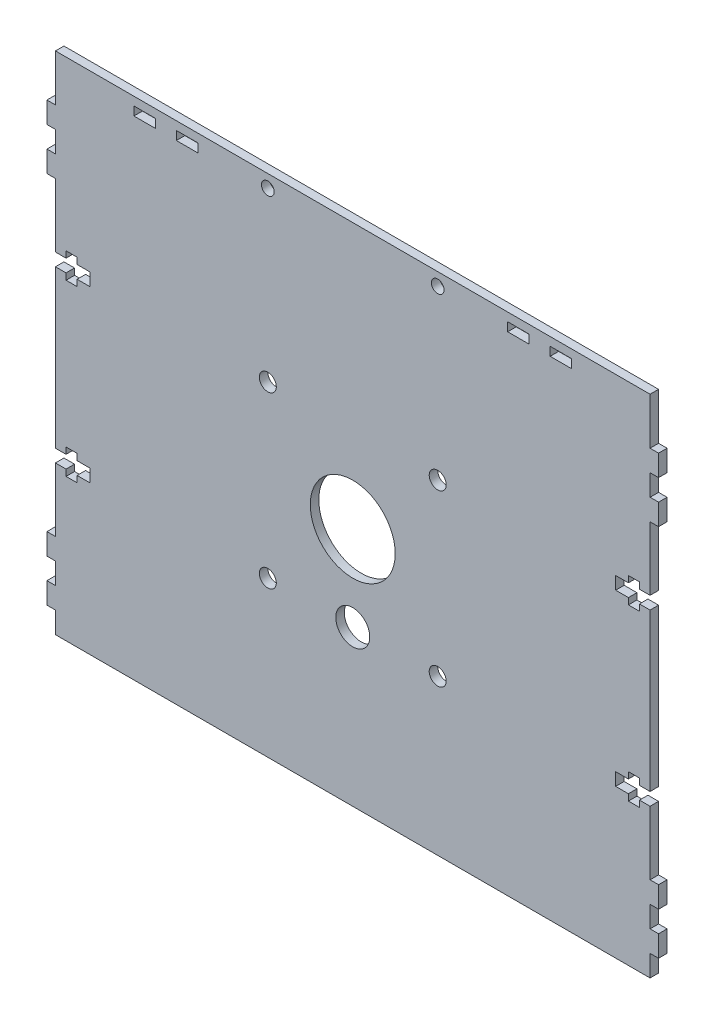
SolidWorks part; units mm, degrees
ref_plane "前视基准面" through (0, 0, 0) normal (0, 0, 1) x (1, 0, 0)
ref_plane "上视基准面" through (0, 0, 0) normal (0, 1, 0) x (1, 0, 0)
ref_plane "右视基准面" through (0, 0, 0) normal (1, 0, 0) x (0, 0, -1)
sketch "草图1" plane through (0, 0, 0) normal (0, 0, 1) x (1, 0, 0)
  line L50 (249.9534, 275.9629) -> (249.9534, 255.9629) construction
  line L53 (317.4534, 257.4629) -> (317.4534, 258.9629)
  line L54 (317.4534, 254.4629) -> (317.4534, 252.9629)
  line L55 (319.9534, 254.4629) -> (317.4534, 254.4629)
  line L56 (317.4534, 258.9629) -> (314.8534, 258.9629)
  line L57 (314.8534, 258.9629) -> (314.8534, 257.4629)
  line L58 (314.8534, 257.4629) -> (311.8534, 257.4629)
  line L59 (311.8534, 254.4629) -> (311.8534, 257.4629)
  line L60 (314.8534, 254.4629) -> (311.8534, 254.4629)
  line L61 (314.8534, 252.9629) -> (314.8534, 254.4629)
  line L62 (317.4534, 252.9629) -> (314.8534, 252.9629)
  line L63 (317.4534, 257.4629) -> (319.9534, 257.4629)
  line L68 (319.9534, 254.4629) -> (319.9534, 257.4629) construction
  line L69 (311.8534, 255.9629) -> (319.9534, 255.9629) construction
  line L73 (311.8534, 295.9629) -> (319.9534, 295.9629) construction
  line L75 (317.4534, 294.4629) -> (319.9534, 294.4629)
  line L76 (317.4534, 298.9629) -> (314.8534, 298.9629)
  line L77 (314.8534, 298.9629) -> (314.8534, 297.4629)
  line L78 (314.8534, 297.4629) -> (311.8534, 297.4629)
  line L79 (311.8534, 297.4629) -> (311.8534, 294.4629)
  line L80 (314.8534, 294.4629) -> (311.8534, 294.4629)
  line L81 (314.8534, 292.9629) -> (314.8534, 294.4629)
  line L82 (317.4534, 292.9629) -> (314.8534, 292.9629)
  line L83 (319.9534, 297.4629) -> (317.4534, 297.4629)
  line L84 (317.4534, 297.4629) -> (317.4534, 298.9629)
  line L85 (317.4534, 294.4629) -> (317.4534, 292.9629)
  line L111 (182.4534, 294.4629) -> (182.4534, 292.9629)
  line L112 (182.4534, 297.4629) -> (182.4534, 298.9629)
  line L113 (179.9534, 297.4629) -> (182.4534, 297.4629)
  line L114 (182.4534, 292.9629) -> (185.0534, 292.9629)
  line L115 (185.0534, 292.9629) -> (185.0534, 294.4629)
  line L116 (185.0534, 294.4629) -> (188.0534, 294.4629)
  line L117 (188.0534, 297.4629) -> (188.0534, 294.4629)
  line L118 (185.0534, 297.4629) -> (188.0534, 297.4629)
  line L119 (185.0534, 298.9629) -> (185.0534, 297.4629)
  line L120 (182.4534, 298.9629) -> (185.0534, 298.9629)
  line L121 (182.4534, 294.4629) -> (179.9534, 294.4629)
  line L122 (182.4534, 257.4629) -> (179.9534, 257.4629)
  line L123 (182.4534, 252.9629) -> (185.0534, 252.9629)
  line L124 (185.0534, 252.9629) -> (185.0534, 254.4629)
  line L125 (185.0534, 254.4629) -> (188.0534, 254.4629)
  line L126 (188.0534, 254.4629) -> (188.0534, 257.4629)
  line L127 (185.0534, 257.4629) -> (188.0534, 257.4629)
  line L128 (185.0534, 258.9629) -> (185.0534, 257.4629)
  line L129 (182.4534, 258.9629) -> (185.0534, 258.9629)
  line L130 (179.9534, 254.4629) -> (182.4534, 254.4629)
  line L131 (182.4534, 254.4629) -> (182.4534, 252.9629)
  line L132 (182.4534, 257.4629) -> (182.4534, 258.9629)
  line L133 (179.9534, 297.4629) -> (179.9534, 294.4629) construction
  line L134 (188.0534, 295.9629) -> (179.9534, 295.9629) construction
  line L135 (188.0534, 255.9629) -> (179.9534, 255.9629) construction
  line L163 (179.9534, 294.4629) -> (179.9534, 257.4629)
  line L172 (319.9534, 257.4629) -> (319.9534, 294.4629)
  line L188 (179.9534, 239.4629) -> (177.9534, 239.4629)
  line L189 (177.9534, 239.4629) -> (177.9534, 234.4629)
  line L190 (177.9534, 234.4629) -> (179.9534, 234.4629)
  line L191 (179.9534, 234.4629) -> (179.9534, 229.4629)
  line L192 (179.9534, 229.4629) -> (177.9534, 229.4629)
  line L193 (177.9534, 229.4629) -> (177.9534, 224.4629)
  line L194 (177.9534, 224.4629) -> (179.9534, 224.4629)
  line L196 (179.9534, 327.4629) -> (179.9534, 345.9629) construction
  line L197 (177.9534, 327.4629) -> (179.9534, 327.4629)
  line L198 (177.9534, 322.4629) -> (177.9534, 327.4629)
  line L199 (179.9534, 322.4629) -> (177.9534, 322.4629)
  line L200 (179.9534, 317.4629) -> (179.9534, 322.4629)
  line L201 (177.9534, 317.4629) -> (179.9534, 317.4629)
  line L202 (177.9534, 312.4629) -> (177.9534, 317.4629)
  line L203 (179.9534, 312.4629) -> (177.9534, 312.4629)
  line L224 (319.9534, 312.4629) -> (321.9534, 312.4629)
  line L225 (321.9534, 312.4629) -> (321.9534, 317.4629)
  line L226 (321.9534, 317.4629) -> (319.9534, 317.4629)
  line L227 (319.9534, 317.4629) -> (319.9534, 322.4629)
  line L228 (319.9534, 322.4629) -> (321.9534, 322.4629)
  line L229 (321.9534, 322.4629) -> (321.9534, 327.4629)
  line L230 (321.9534, 327.4629) -> (319.9534, 327.4629)
  line L233 (321.9534, 224.4629) -> (319.9534, 224.4629)
  line L234 (321.9534, 229.4629) -> (321.9534, 224.4629)
  line L235 (319.9534, 229.4629) -> (321.9534, 229.4629)
  line L236 (319.9534, 234.4629) -> (319.9534, 229.4629)
  line L237 (321.9534, 234.4629) -> (319.9534, 234.4629)
  line L238 (321.9534, 239.4629) -> (321.9534, 234.4629)
  line L239 (319.9534, 239.4629) -> (321.9534, 239.4629)
  line L261 (249.9534, 255.9629) -> (229.9534, 255.9629) construction
  line L262 (319.9534, 327.4629) -> (319.9534, 330.9829)
  line L268 (179.9534, 297.4629) -> (179.9534, 312.4629)
  line L271 (319.9534, 312.4629) -> (319.9534, 297.4629)
  line L272 (319.9534, 254.4629) -> (319.9534, 239.4629)
  line L275 (179.9534, 239.4629) -> (179.9534, 254.4629)
  line L279 (317.4534, 330.9829) -> (317.4534, 345.9629) construction
  line L280 (317.4534, 345.9629) -> (179.9534, 345.9629) construction
  line L285 (317.4534, 338.4729) -> (179.9534, 338.4729)
  line L286 (179.9534, 327.4629) -> (179.9534, 338.4729)
  line L288 (317.4534, 338.4729) -> (319.9534, 338.4729)
  line L289 (319.9534, 338.4729) -> (319.9534, 330.9829)
  line L290 (319.9534, 219.4409) -> (179.9534, 219.4409)
  line L291 (179.9534, 219.4409) -> (179.9534, 224.4629)
  line L292 (319.9534, 219.4409) -> (319.9534, 224.4629)
  line L310 (203.4784, 334.4379) -> (198.4284, 336.4879) construction
  line L311 (286.4284, 336.4879) -> (291.4784, 336.4879)
  line L312 (286.4284, 336.4879) -> (286.4284, 334.4379)
  line L313 (286.4284, 334.4379) -> (291.4784, 334.4379)
  line L314 (291.4784, 336.4879) -> (291.4784, 334.4379)
  line L315 (286.4284, 336.4879) -> (291.4784, 334.4379) construction
  line L316 (286.4284, 334.4379) -> (291.4784, 336.4879) construction
  line L317 (296.4284, 336.4879) -> (301.4784, 336.4879)
  line L318 (296.4284, 336.4879) -> (296.4284, 334.4379)
  line L319 (296.4284, 334.4379) -> (301.4784, 334.4379)
  line L320 (301.4784, 336.4879) -> (301.4784, 334.4379)
  line L321 (296.4284, 336.4879) -> (301.4784, 334.4379) construction
  line L322 (296.4284, 334.4379) -> (301.4784, 336.4879) construction
  line L323 (268.4534, 343.4629) -> (266.9534, 343.4629) [skipped]
  line L324 (271.4534, 343.4629) -> (272.9534, 343.4629) [skipped]
  line L325 (271.4534, 345.9629) -> (271.4534, 343.4629) [skipped]
  line L326 (266.9534, 343.4629) -> (266.9534, 340.8629) [skipped]
  line L327 (266.9534, 340.8629) -> (268.4534, 340.8629) [skipped]
  line L328 (268.4534, 340.8629) -> (268.4534, 337.8629) [skipped]
  line L329 (271.4534, 340.8629) -> (271.4534, 337.8629) [skipped]
  line L330 (272.9534, 340.8629) -> (271.4534, 340.8629) [skipped]
  line L331 (272.9534, 343.4629) -> (272.9534, 340.8629) [skipped]
  line L332 (268.4534, 343.4629) -> (268.4534, 345.9629) [skipped]
  line L333 (231.4534, 343.4629) -> (231.4534, 345.9629) [skipped]
  line L334 (226.9534, 343.4629) -> (226.9534, 340.8629) [skipped]
  line L335 (226.9534, 340.8629) -> (228.4534, 340.8629) [skipped]
  line L336 (228.4534, 340.8629) -> (228.4534, 337.8629) [skipped]
  line L337 (231.4534, 340.8629) -> (231.4534, 337.8629) [skipped]
  line L338 (232.9534, 340.8629) -> (231.4534, 340.8629) [skipped]
  line L339 (232.9534, 343.4629) -> (232.9534, 340.8629) [skipped]
  line L340 (228.4534, 345.9629) -> (228.4534, 343.4629) [skipped]
  line L341 (228.4534, 343.4629) -> (226.9534, 343.4629) [skipped]
  line L342 (231.4534, 343.4629) -> (232.9534, 343.4629) [skipped]
  line L343 (268.4534, 345.9629) -> (231.4534, 345.9629) [skipped]
  line L344 (213.4534, 345.9629) -> (213.4534, 347.9629) [skipped]
  line L345 (213.4534, 347.9629) -> (208.4534, 347.9629) [skipped]
  line L346 (208.4534, 347.9629) -> (208.4534, 345.9629) [skipped]
  line L347 (208.4534, 345.9629) -> (203.4534, 345.9629) [skipped]
  line L348 (203.4534, 345.9629) -> (203.4534, 347.9629) [skipped]
  line L349 (203.4534, 347.9629) -> (198.4534, 347.9629) [skipped]
  line L350 (198.4534, 347.9629) -> (198.4534, 345.9629) [skipped]
  line L352 (301.4534, 345.9629) -> (319.9534, 345.9629) [skipped]
  line L353 (301.4534, 347.9629) -> (301.4534, 345.9629) [skipped]
  line L354 (296.4534, 347.9629) -> (301.4534, 347.9629) [skipped]
  line L355 (296.4534, 345.9629) -> (296.4534, 347.9629) [skipped]
  line L356 (291.4534, 345.9629) -> (296.4534, 345.9629) [skipped]
  line L357 (291.4534, 347.9629) -> (291.4534, 345.9629) [skipped]
  line L358 (286.4534, 347.9629) -> (291.4534, 347.9629) [skipped]
  line L359 (286.4534, 345.9629) -> (286.4534, 347.9629) [skipped]
  line L360 (271.4534, 345.9629) -> (268.4534, 345.9629) construction
  line L361 (269.9534, 337.8629) -> (269.9534, 345.9629) construction
  line L362 (229.9534, 337.8629) -> (229.9534, 345.9629) construction
  line L363 (271.4534, 337.8629) -> (268.4534, 337.8629) [skipped]
  line L364 (228.4534, 337.8629) -> (231.4534, 337.8629) [skipped]
  line L365 (203.4784, 336.4879) -> (198.4284, 334.4379) construction
  line L366 (213.4784, 334.4379) -> (208.4284, 336.4879) construction
  line L367 (213.4784, 336.4879) -> (208.4284, 334.4379) construction
  line L368 (198.4284, 336.4879) -> (198.4284, 334.4379)
  line L369 (203.4784, 334.4379) -> (198.4284, 334.4379)
  line L370 (203.4784, 336.4879) -> (203.4784, 334.4379)
  line L371 (203.4784, 336.4879) -> (198.4284, 336.4879)
  line L372 (208.4284, 336.4879) -> (208.4284, 334.4379)
  line L373 (213.4784, 334.4379) -> (208.4284, 334.4379)
  line L374 (213.4784, 336.4879) -> (213.4784, 334.4379)
  line L375 (213.4784, 336.4879) -> (208.4284, 336.4879)
  line L377 (231.4534, 208.4629) -> (232.9534, 208.4629) [skipped]
  line L378 (228.4534, 208.4629) -> (226.9534, 208.4629) [skipped]
  line L379 (228.4534, 205.9629) -> (228.4534, 208.4629) [skipped]
  line L380 (232.9534, 208.4629) -> (232.9534, 211.0629) [skipped]
  line L381 (232.9534, 211.0629) -> (231.4534, 211.0629) [skipped]
  line L382 (231.4534, 211.0629) -> (231.4534, 214.0629) [skipped]
  line L383 (228.4534, 214.0629) -> (231.4534, 214.0629) [skipped]
  line L384 (228.4534, 211.0629) -> (228.4534, 214.0629) [skipped]
  line L385 (226.9534, 211.0629) -> (228.4534, 211.0629) [skipped]
  line L386 (226.9534, 208.4629) -> (226.9534, 211.0629) [skipped]
  line L387 (231.4534, 208.4629) -> (231.4534, 205.9629) [skipped]
  line L388 (268.4534, 208.4629) -> (268.4534, 205.9629) [skipped]
  line L389 (272.9534, 208.4629) -> (272.9534, 211.0629) [skipped]
  line L390 (272.9534, 211.0629) -> (271.4534, 211.0629) [skipped]
  line L391 (271.4534, 211.0629) -> (271.4534, 214.0629) [skipped]
  line L392 (271.4534, 214.0629) -> (268.4534, 214.0629) [skipped]
  line L393 (268.4534, 211.0629) -> (268.4534, 214.0629) [skipped]
  line L394 (266.9534, 211.0629) -> (268.4534, 211.0629) [skipped]
  line L395 (266.9534, 208.4629) -> (266.9534, 211.0629) [skipped]
  line L396 (271.4534, 205.9629) -> (271.4534, 208.4629) [skipped]
  line L397 (271.4534, 208.4629) -> (272.9534, 208.4629) [skipped]
  line L398 (268.4534, 208.4629) -> (266.9534, 208.4629) [skipped]
  line L399 (231.4534, 205.9629) -> (268.4534, 205.9629) [skipped]
  line L400 (286.4534, 205.9629) -> (286.4534, 203.9629) [skipped]
  line L401 (286.4534, 203.9629) -> (291.4534, 203.9629) [skipped]
  line L402 (291.4534, 203.9629) -> (291.4534, 205.9629) [skipped]
  line L403 (291.4534, 205.9629) -> (296.4534, 205.9629) [skipped]
  line L404 (296.4534, 205.9629) -> (296.4534, 203.9629) [skipped]
  line L405 (296.4534, 203.9629) -> (301.4534, 203.9629) [skipped]
  line L406 (301.4534, 203.9629) -> (301.4534, 205.9629) [skipped]
  line L408 (198.4534, 205.9629) -> (179.9534, 205.9629) [skipped]
  line L409 (198.4534, 203.9629) -> (198.4534, 205.9629) [skipped]
  line L410 (203.4534, 203.9629) -> (198.4534, 203.9629) [skipped]
  line L411 (203.4534, 205.9629) -> (203.4534, 203.9629) [skipped]
  line L412 (208.4534, 205.9629) -> (203.4534, 205.9629) [skipped]
  line L413 (208.4534, 203.9629) -> (208.4534, 205.9629) [skipped]
  line L414 (213.4534, 203.9629) -> (208.4534, 203.9629) [skipped]
  line L415 (213.4534, 205.9629) -> (213.4534, 203.9629) [skipped]
  line L416 (228.4534, 205.9629) -> (231.4534, 205.9629) construction
  line L417 (229.9534, 214.0629) -> (229.9534, 205.9629) construction
  line L418 (269.9534, 214.0629) -> (269.9534, 205.9629) construction
  line L419 (319.9534, 224.4629) -> (319.9534, 205.9629) [skipped]
  circle A14 centre (249.9534, 275.9629) radius 10
  circle A24 centre (249.9534, 255.9629) radius 4
  circle A27 centre (229.9534, 335.4629) radius 1.5
  circle A28 centre (269.9534, 335.4629) radius 1.5
  circle A29 centre (229.9534, 255.9629) radius 2
  circle A30 centre (229.9534, 295.9629) radius 2
  circle A31 centre (269.9534, 295.9629) radius 2
  circle A32 centre (269.9534, 255.9629) radius 2
  point P107 (210.9534, 335.4629)
  point P232 (288.9534, 335.4629)
  dimension "D1" = 7.49
  dimension "D5" = 4
  dimension "D4" = 4
extrude "凸台-拉伸1" add sketch "草图1" along normal blind 2
sketch "草图2" plane through (179.9534, 0, 0) normal (-1, 0, 0) x (0, 0, 1)
  line L0 (1, 294.4629) -> (1, 297.4629) construction
  line L1 (2, 294.4629) -> (0, 294.4629) construction
  line L2 (2, 297.4629) -> (0, 297.4629) construction
  line L3 (1, 295.9629) -> (1, 312.4629) construction
  line L4 (2, 312.4629) -> (0, 312.4629) construction
  circle A0 centre (1, 295.9629) radius 1.5
sketch "草图4" plane through (319.9534, 0, 0) normal (1, 0, 0) x (0, 0, -1)
  line L0 (-1, 257.4629) -> (-1, 254.4629) construction
  line L1 (-2, 257.4629) -> (0, 257.4629) construction
  line L2 (-2, 254.4629) -> (0, 254.4629) construction
  circle A0 centre (-1, 255.9629) radius 1.5
sketch "草图5" plane through (0, 205.9629, 0) normal (0, -1, 0) x (1, 0, 0)
  line L0 (231.4534, 1) -> (228.4534, 1) construction
  line L1 (231.4534, 2) -> (231.4534, 0) construction
  line L2 (228.4534, 2) -> (228.4534, 0) construction
  circle A0 centre (229.9534, 1) radius 1.5
